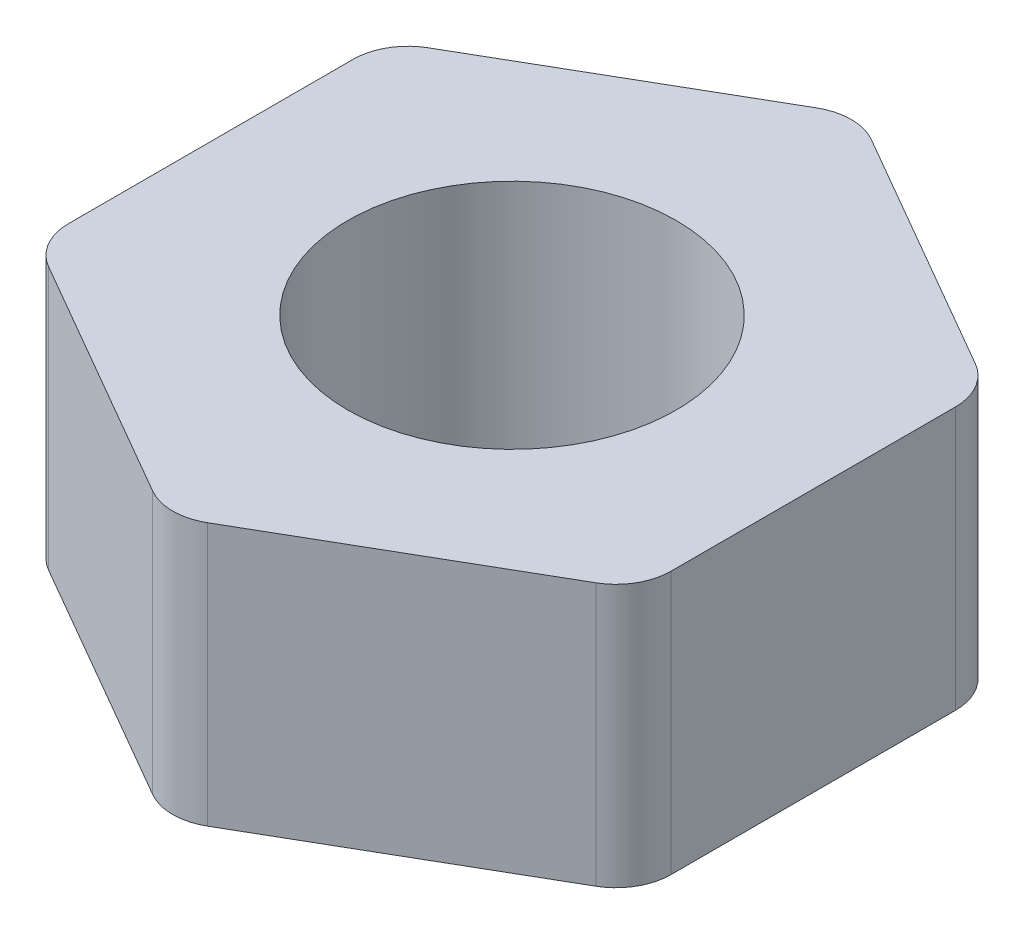
SolidWorks part; units mm, degrees
ref_plane "前视基准面" through (0, 0, 0) normal (0, 0, 1) x (1, 0, 0)
ref_plane "上视基准面" through (0, 0, 0) normal (0, 1, 0) x (1, 0, 0)
ref_plane "右视基准面" through (0, 0, 0) normal (1, 0, 0) x (0, 0, -1)
sketch "草图1" plane through (0, 0, 0) normal (0, 1, 0) x (1, 0, 0)
  line L1 (0, 3.1754) -> (-2.75, 1.5877)
  line L2 (-2.75, 1.5877) -> (-2.75, -1.5877)
  line L3 (-2.75, -1.5877) -> (0, -3.1754)
  line L4 (0, -3.1754) -> (2.75, -1.5877)
  line L5 (2.75, -1.5877) -> (2.75, 1.5877)
  line L6 (2.75, 1.5877) -> (0, 3.1754)
  circle A0 centre (0, 0) radius 2.75 construction
  circle A1 centre (0, 0) radius 1.5
  dimension "D2" = 3
  dimension "D1" = 5.5
extrude "凸台-拉伸1" add sketch "草图1" along normal blind 2.4
fillet "圆角1" radius 0.5 6 edges at (-2.75, 1.2, -1.5877) (0, 1.2, -3.1754) (2.75, 1.2, -1.5877) (2.75, 1.2, 1.5877) (0, 1.2, 3.1754) (-2.75, 1.2, 1.5877)
